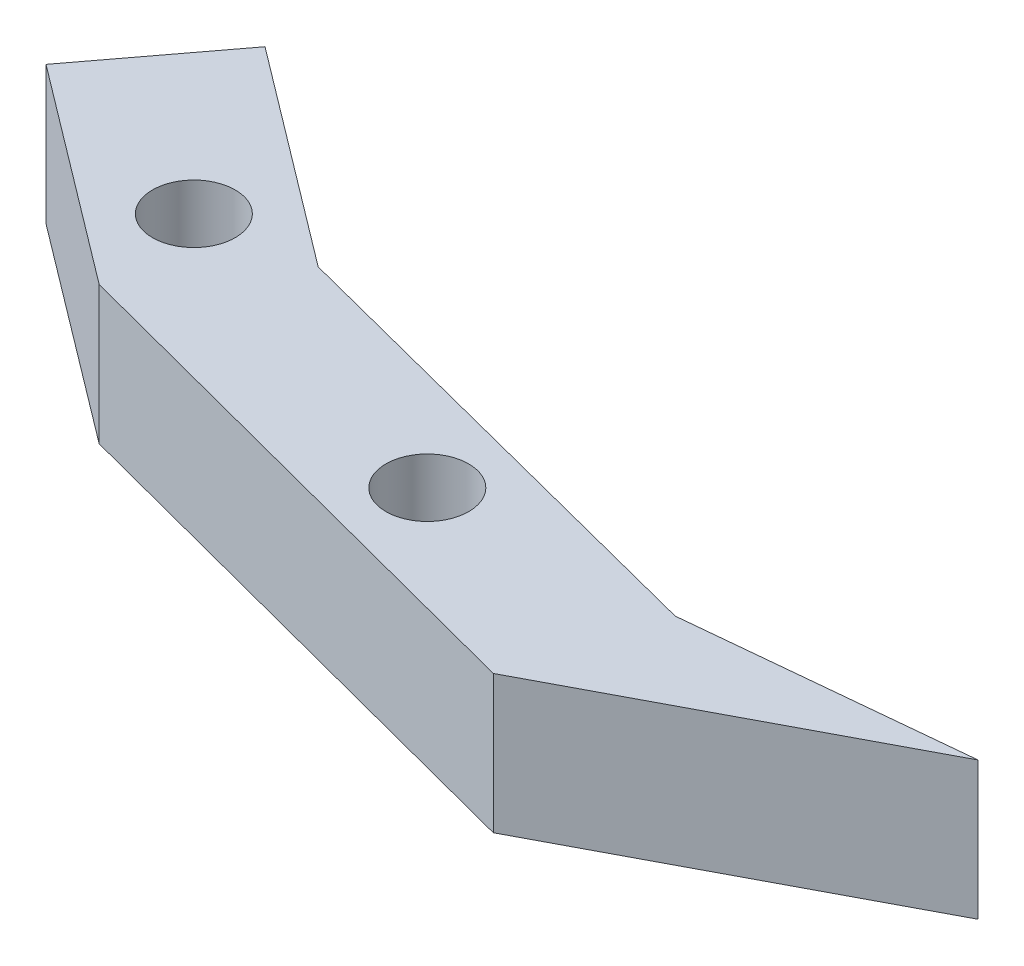
SolidWorks part; units mm, degrees
ref_plane "前视基准面" through (0, 0, 0) normal (0, 0, 1) x (1, 0, 0)
ref_plane "上视基准面" through (0, 0, 0) normal (0, 1, 0) x (1, 0, 0)
ref_plane "右视基准面" through (0, 0, 0) normal (1, 0, 0) x (0, 0, -1)
sketch "草图1" plane through (0, 0, 0) normal (0, 1, 0) x (1, 0, 0)
  line L0 (-34.4562, -3.4942) -> (-26.5841, -9.4389)
  line L1 (-31.0415, 1.0276) -> (-23.1694, -4.9172)
  line L2 (-23.1694, -4.9172) -> (-5.7388, -9.4088)
  line L3 (-5.7388, -9.4088) -> (4.2612, -8.4371)
  line L4 (-7.2361, -14.5043) -> (4.2612, -8.4371)
  line L5 (-26.5841, -9.4389) -> (-7.2361, -14.5043)
  line L9 (-31.0415, 1.0276) -> (-34.4562, -3.4942)
  circle A0 centre (-27.0876, -5.5046) radius 1.5
  circle A1 centre (-14.2599, -9.8722) radius 1.5
  dimension "D4" = 3
  dimension "D5" = 3
  dimension "D1" = 5.6663
  dimension "D2" = 0.221
  dimension "D3" = 2.83
extrude "凸台-拉伸1" add sketch "草图1" along normal blind 5
